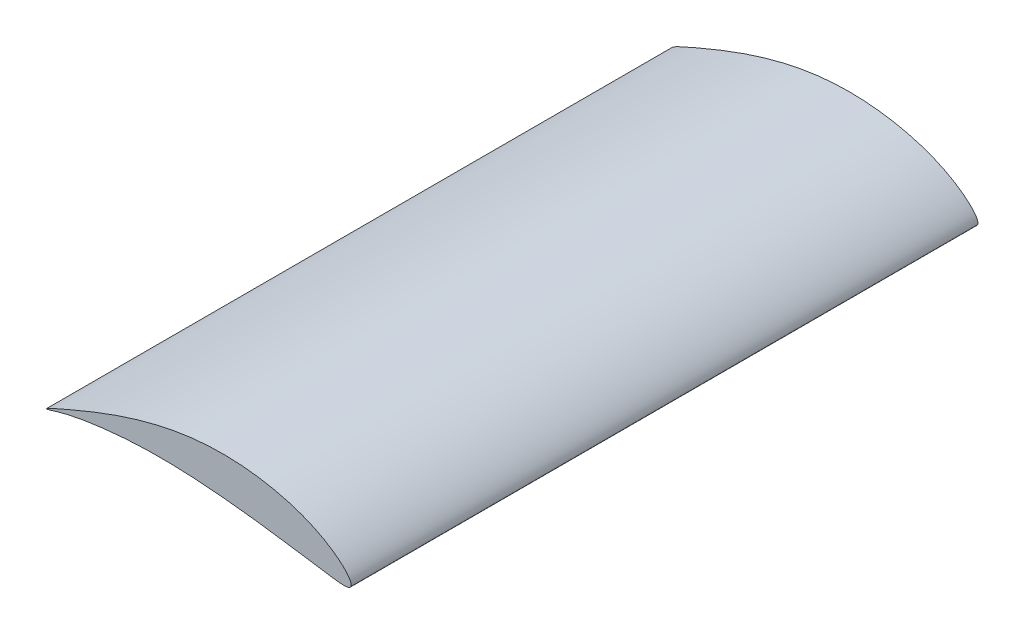
SolidWorks part; units mm, degrees
ref_plane "Front Plane" through (0, 0, 0) normal (0, 0, 1) x (1, 0, 0)
ref_plane "Top Plane" through (0, 0, 0) normal (0, 1, 0) x (1, 0, 0)
ref_plane "Right Plane" through (0, 0, 0) normal (1, 0, 0) x (0, 0, -1)
curve "Curve1"
  spline degree 3 poles (1000, 0.05, 0) (999.1829, 0.6011, 0) (996.1617, 2.6385, 0) (989.6861, 6.4695, 0) (979.4885, 11.6604, 0) (965.9541, 17.6688, 0) (949.3697, 25.0032, 0) (929.6562, 33.6439, 0) (906.8358, 43.3305, 0) (881.204, 54.0512, 0) (853.0123, 65.5684, 0) (822.5289, 77.572, 0) (790.0341, 89.7094, 0) (755.8325, 101.6996, 0) (720.2048, 113.218, 0) (683.4739, 124.0706, 0) (645.9247, 133.9661, 0) (607.8441, 142.6615, 0) (569.5107, 149.9434, 0) (531.1053, 155.6359, 0) (492.7339, 159.7002, 0) (454.4928, 162.0318, 0) (416.5285, 162.6903, 0) (379.0542, 161.6162, 0) (342.2545, 158.9176, 0) (306.3308, 154.6435, 0) (271.4852, 148.9086, 0) (237.9154, 141.8256, 0) (205.8269, 133.4665, 0) (175.4036, 123.9664, 0) (146.8608, 113.3595, 0) (120.3879, 101.8165, 0) (96.1828, 89.4969, 0) (74.4062, 76.6835, 0) (55.1678, 63.7572, 0) (38.5732, 51.0199, 0) (24.7414, 38.681, 0) (13.7422, 27.0098, 0) (5.7259, 16.3369, 0) (1.1316, 7.464, 0) (-0.3413, 0.5275, 0) (0.6801, -5.286, 0) (5.779, -10.0394, 0) (14.2306, -12.2508, 0) (25.2642, -12.9429, 0) (39.0829, -12.1563, 0) (55.612, -10.2426, 0) (74.8087, -7.4867, 0) (96.5644, -4.2188, 0) (120.7468, -0.6594, 0) (147.1705, 3.3036, 0) (175.6679, 7.5773, 0) (206.0348, 12.1109, 0) (238.084, 16.7688, 0) (271.6128, 21.4594, 0) (306.4234, 26.0657, 0) (342.3122, 30.4922, 0) (379.0741, 34.6631, 0) (416.5109, 38.4809, 0) (454.438, 41.8763, 0) (492.6428, 44.7613, 0) (530.9859, 47.0458, 0) (569.368, 48.6362, 0) (607.6922, 49.4681, 0) (645.7749, 49.4651, 0) (683.3357, 48.6109, 0) (720.0839, 46.8753, 0) (755.7212, 44.3961, 0) (789.9457, 41.2494, 0) (822.4681, 37.5905, 0) (852.9885, 33.4435, 0) (881.2165, 28.9292, 0) (906.8664, 24.1451, 0) (929.6798, 19.281, 0) (949.4481, 14.4993, 0) (965.9949, 9.7527, 0) (979.3179, 5.4428, 0) (989.484, 2.3849, 0) (996.0555, 0.7232, 0) (999.1792, 0.103, 0) (1000, -0.06, 0) knots 0 0 0 0 0.001413 0.005226 0.010781 0.017816 0.026461 0.036791 0.048686 0.062017 0.076639 0.092363 0.109003 0.126387 0.144339 0.162701 0.181313 0.200023 0.218713 0.237261 0.255692 0.274037 0.292193 0.310133 0.327788 0.345097 0.362002 0.378421 0.394287 0.409543 0.424114 0.437938 0.450942 0.463044 0.474154 0.484165 0.493024 0.500713 0.507126 0.51213 0.514904 0.517171 0.520262 0.524245 0.529498 0.536092 0.544061 0.553363 0.563905 0.575615 0.58842 0.602227 0.616944 0.632457 0.648676 0.665501 0.682818 0.700538 0.718564 0.736789 0.755151 0.773513 0.791878 0.810245 0.828489 0.846493 0.864125 0.881249 0.897725 0.913415 0.928184 0.941897 0.954411 0.965603 0.97535 0.983576 0.990285 0.995433 0.9988 1 1 1 1
sketch "Sketch3" plane through (0, 0, 0) normal (0, 0, -1) x (-1, 0, 0)
  line L0 (1000, 0.05) -> (1000, -0.06)
  line L1 (1000, -0.06) -> (0, 0) construction
  line L2 (280, 0.014) -> (280, -0.0168)
  spline S1 degree 3 poles (280, 0.014) (279.7712, 0.1683) (278.9253, 0.7388) (277.1121, 1.8115) (274.2568, 3.2649) (270.4672, 4.9473) (265.8235, 7.0009) (260.3037, 9.4203) (253.914, 12.1325) (246.7371, 15.1343) (238.8434, 18.3592) (230.3081, 21.7202) (221.2095, 25.1186) (211.6331, 28.4759) (201.6573, 31.7011) (191.3727, 34.7398) (180.8589, 37.5105) (170.1963, 39.9452) (159.463, 41.9841) (148.7095, 43.578) (137.9655, 44.716) (127.258, 45.3689) (116.628, 45.5533) (106.1352, 45.2525) (95.8313, 44.4969) (85.7726, 43.3002) (76.0158, 41.6944) (66.6163, 39.7112) (57.6315, 37.3706) (49.113, 34.7106) (41.121, 31.7407) (33.7086, 28.5086) (26.9312, 25.0591) (20.8337, 21.4714) (15.447, 17.852) (10.8005, 14.2856) (6.9276, 10.8307) (3.8478, 7.5627) (1.6032, 4.5743) (0.3168, 2.0899) (-0.0956, 0.1477) (0.1904, -1.4801) (1.6181, -2.811) (3.9846, -3.4302) (7.074, -3.624) (10.9432, -3.4038) (15.5714, -2.8679) (20.9464, -2.0963) (27.038, -1.1813) (33.8091, -0.1846) (41.2077, 0.925) (49.187, 2.1216) (57.6898, 3.3911) (66.6635, 4.6953) (76.0516, 6.0086) (85.7986, 7.2984) (95.8474, 8.5378) (106.1407, 9.7057) (116.6231, 10.7746) (127.2426, 11.7254) (137.94, 12.5332) (148.676, 13.1728) (159.423, 13.6181) (170.1538, 13.8511) (180.817, 13.8502) (191.334, 13.6111) (201.6235, 13.1251) (211.6019, 12.4309) (221.1848, 11.5498) (230.2911, 10.5253) (238.8368, 9.3642) (246.7406, 8.1002) (253.9226, 6.7606) (260.3103, 5.3987) (265.8455, 4.0598) (270.4786, 2.7307) (274.209, 1.524) (277.0555, 0.6678) (278.8955, 0.2025) (279.7702, 0.0288) (280, -0.0168) knots 0 0 0 0 0.001413 0.005226 0.010781 0.017816 0.026461 0.036791 0.048686 0.062017 0.076639 0.092363 0.109003 0.126387 0.144339 0.162701 0.181313 0.200023 0.218713 0.237261 0.255692 0.274037 0.292193 0.310133 0.327788 0.345097 0.362002 0.378421 0.394287 0.409543 0.424114 0.437938 0.450942 0.463044 0.474154 0.484165 0.493024 0.500713 0.507126 0.51213 0.514904 0.517171 0.520262 0.524245 0.529498 0.536092 0.544061 0.553363 0.563905 0.575615 0.58842 0.602227 0.616944 0.632457 0.648676 0.665501 0.682818 0.700538 0.718564 0.736789 0.755151 0.773513 0.791878 0.810245 0.828489 0.846493 0.864125 0.881249 0.897725 0.913415 0.928184 0.941897 0.954411 0.965603 0.97535 0.983576 0.990285 0.995433 0.9988 1 1 1 1
  dimension "D2" = 280
  dimension "D3" = 1000
  dimension "D4" = 0.014
  dimension "D5" = 0.05
  dimension "D6" = 0.0168
ref_plane "Plane1" through (0, 0, 575) normal (0, 0, 1) x (1, 0, 0)
sketch "Sketch6" plane through (0, 0, 575) normal (0, 0, 1) x (1, 0, 0)
  line L0 (-280, 0.014) -> (-280, -0.0168)
  spline S0 degree 3 poles (-1425.9906, 1638.1292) (-300.6745, -45.3243) (-297.1807, -10.061) (-277.1121, 1.8115) (-274.2568, 3.2649) (-270.4672, 4.9473) (-265.8235, 7.0009) (-260.3037, 9.4203) (-253.914, 12.1325) (-246.7371, 15.1343) (-238.8434, 18.3592) (-230.3081, 21.7202) (-221.2095, 25.1186) (-211.6331, 28.4759) (-201.6573, 31.7011) (-191.3727, 34.7398) (-180.8589, 37.5105) (-170.1963, 39.9452) (-159.463, 41.9841) (-148.7095, 43.578) (-137.9655, 44.716) (-127.258, 45.3689) (-116.628, 45.5533) (-106.1352, 45.2525) (-95.8313, 44.4969) (-85.7726, 43.3002) (-76.0158, 41.6944) (-66.6163, 39.7112) (-57.6315, 37.3706) (-49.113, 34.7106) (-41.121, 31.7407) (-33.7086, 28.5086) (-26.9312, 25.0591) (-20.8337, 21.4714) (-15.447, 17.852) (-10.8005, 14.2856) (-6.9276, 10.8307) (-3.8478, 7.5627) (-1.6032, 4.5743) (-0.3168, 2.0899) (0.0956, 0.1477) (-0.1904, -1.4801) (-1.6181, -2.811) (-3.9846, -3.4302) (-7.074, -3.624) (-10.9432, -3.4038) (-15.5714, -2.8679) (-20.9464, -2.0963) (-27.038, -1.1813) (-33.8091, -0.1846) (-41.2077, 0.925) (-49.187, 2.1216) (-57.6898, 3.3911) (-66.6635, 4.6953) (-76.0516, 6.0086) (-85.7986, 7.2984) (-95.8474, 8.5378) (-106.1407, 9.7057) (-116.6231, 10.7746) (-127.2426, 11.7254) (-137.94, 12.5332) (-148.676, 13.1728) (-159.423, 13.6181) (-170.1538, 13.8511) (-180.817, 13.8502) (-191.334, 13.6111) (-201.6235, 13.1251) (-211.6019, 12.4309) (-221.1848, 11.5498) (-230.2911, 10.5253) (-238.8368, 9.3642) (-246.7406, 8.1002) (-253.9226, 6.7606) (-260.3103, 5.3987) (-265.8455, 4.0598) (-270.4786, 2.7307) (-274.209, 1.524) (-277.0555, 0.6678) (-298.3619, -4.7199) (-324.0084, 15.0445) (78.2537, -1967.1141) knots -0.108546 -0.108546 -0.108546 -0.108546 0.001413 0.005226 0.010781 0.017816 0.026461 0.036791 0.048686 0.062017 0.076639 0.092363 0.109003 0.126387 0.144339 0.162701 0.181313 0.200023 0.218713 0.237261 0.255692 0.274037 0.292193 0.310133 0.327788 0.345097 0.362002 0.378421 0.394287 0.409543 0.424114 0.437938 0.450942 0.463044 0.474154 0.484165 0.493024 0.500713 0.507126 0.51213 0.514904 0.517171 0.520262 0.524245 0.529498 0.536092 0.544061 0.553363 0.563905 0.575615 0.58842 0.602227 0.616944 0.632457 0.648676 0.665501 0.682818 0.700538 0.718564 0.736789 0.755151 0.773513 0.791878 0.810245 0.828489 0.846493 0.864125 0.881249 0.897725 0.913415 0.928184 0.941897 0.954411 0.965603 0.97535 0.983576 0.990285 0.995433 0.9988 1.102784 1.102784 1.102784 1.102784 only from (-280, 0.014) to (-280, -0.0168) construction
  spline S1 degree 3 poles (-280, 0.014) (-279.7712, 0.1683) (-278.9253, 0.7388) (-277.1121, 1.8115) (-274.2568, 3.2649) (-270.4672, 4.9473) (-265.8235, 7.0009) (-260.3037, 9.4203) (-253.914, 12.1325) (-246.7371, 15.1343) (-238.8434, 18.3592) (-230.3081, 21.7202) (-221.2095, 25.1186) (-211.6331, 28.4759) (-201.6573, 31.7011) (-191.3727, 34.7398) (-180.8589, 37.5105) (-170.1963, 39.9452) (-159.463, 41.9841) (-148.7095, 43.578) (-137.9655, 44.716) (-127.258, 45.3689) (-116.628, 45.5533) (-106.1352, 45.2525) (-95.8313, 44.4969) (-85.7726, 43.3002) (-76.0158, 41.6944) (-66.6163, 39.7112) (-57.6315, 37.3706) (-49.113, 34.7106) (-41.121, 31.7407) (-33.7086, 28.5086) (-26.9312, 25.0591) (-20.8337, 21.4714) (-15.447, 17.852) (-10.8005, 14.2856) (-6.9276, 10.8307) (-3.8478, 7.5627) (-1.6032, 4.5743) (-0.3168, 2.0899) (0.0956, 0.1477) (-0.1904, -1.4801) (-1.6181, -2.811) (-3.9846, -3.4302) (-7.074, -3.624) (-10.9432, -3.4038) (-15.5714, -2.8679) (-20.9464, -2.0963) (-27.038, -1.1813) (-33.8091, -0.1846) (-41.2077, 0.925) (-49.187, 2.1216) (-57.6898, 3.3911) (-66.6635, 4.6953) (-76.0516, 6.0086) (-85.7986, 7.2984) (-95.8474, 8.5378) (-106.1407, 9.7057) (-116.6231, 10.7746) (-127.2426, 11.7254) (-137.94, 12.5332) (-148.676, 13.1728) (-159.423, 13.6181) (-170.1538, 13.8511) (-180.817, 13.8502) (-191.334, 13.6111) (-201.6235, 13.1251) (-211.6019, 12.4309) (-221.1848, 11.5498) (-230.2911, 10.5253) (-238.8368, 9.3642) (-246.7406, 8.1002) (-253.9226, 6.7606) (-260.3103, 5.3987) (-265.8455, 4.0598) (-270.4786, 2.7307) (-274.209, 1.524) (-277.0555, 0.6678) (-278.8955, 0.2025) (-279.7702, 0.0288) (-280, -0.0168) knots 0 0 0 0 0.001413 0.005226 0.010781 0.017816 0.026461 0.036791 0.048686 0.062017 0.076639 0.092363 0.109003 0.126387 0.144339 0.162701 0.181313 0.200023 0.218713 0.237261 0.255692 0.274037 0.292193 0.310133 0.327788 0.345097 0.362002 0.378421 0.394287 0.409543 0.424114 0.437938 0.450942 0.463044 0.474154 0.484165 0.493024 0.500713 0.507126 0.51213 0.514904 0.517171 0.520262 0.524245 0.529498 0.536092 0.544061 0.553363 0.563905 0.575615 0.58842 0.602227 0.616944 0.632457 0.648676 0.665501 0.682818 0.700538 0.718564 0.736789 0.755151 0.773513 0.791878 0.810245 0.828489 0.846493 0.864125 0.881249 0.897725 0.913415 0.928184 0.941897 0.954411 0.965603 0.97535 0.983576 0.990285 0.995433 0.9988 1 1 1 1
loft "Loft2" add profiles "Sketch6" section "Sketch6" section "Sketch3"
ref_plane "Plane_Wing_AC" through (-70, 0, 0) normal (1, 0, 0) x (0, 0, -1)
